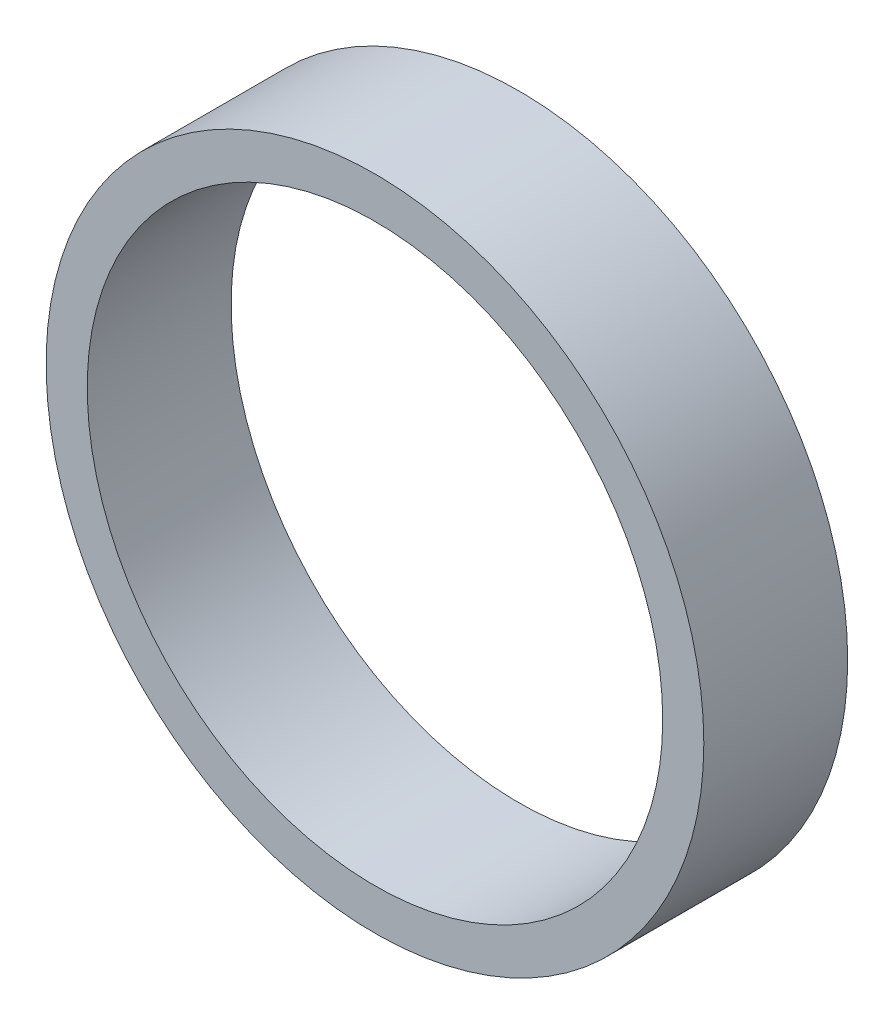
SolidWorks part; units mm, degrees
material "Leaded Commercial Bronze"
ref_plane "Front Plane" through (0, 0, 0) normal (0, 0, 1) x (1, 0, 0)
ref_plane "Top Plane" through (0, 0, 0) normal (0, 1, 0) x (1, 0, 0)
ref_plane "Right Plane" through (0, 0, 0) normal (1, 0, 0) x (0, 0, -1)
sketch "Sketch1" plane through (0, 0, 0) normal (0, 0, 1) x (1, 0, 0)
  circle A0 centre (0, 0) radius 50.8
  circle A1 centre (0, 0) radius 44.45
  dimension "D1" = 101.6
  dimension "D2" = 88.9
extrude "Boss-Extrude1" add sketch "Sketch1" along normal mid plane 22.225
sketch "Sketch2" plane through (0, 0, 0) normal (0, 1, 0) x (1, 0, 0)
  circle A0 centre (0, 0) radius 1.5875
  dimension "D1" = 3.175
extrude "Cut-Extrude1" [suppressed] cut sketch "Sketch2" along normal through all
pattern_circular "CirPattern1" [suppressed] count 4 over 360
